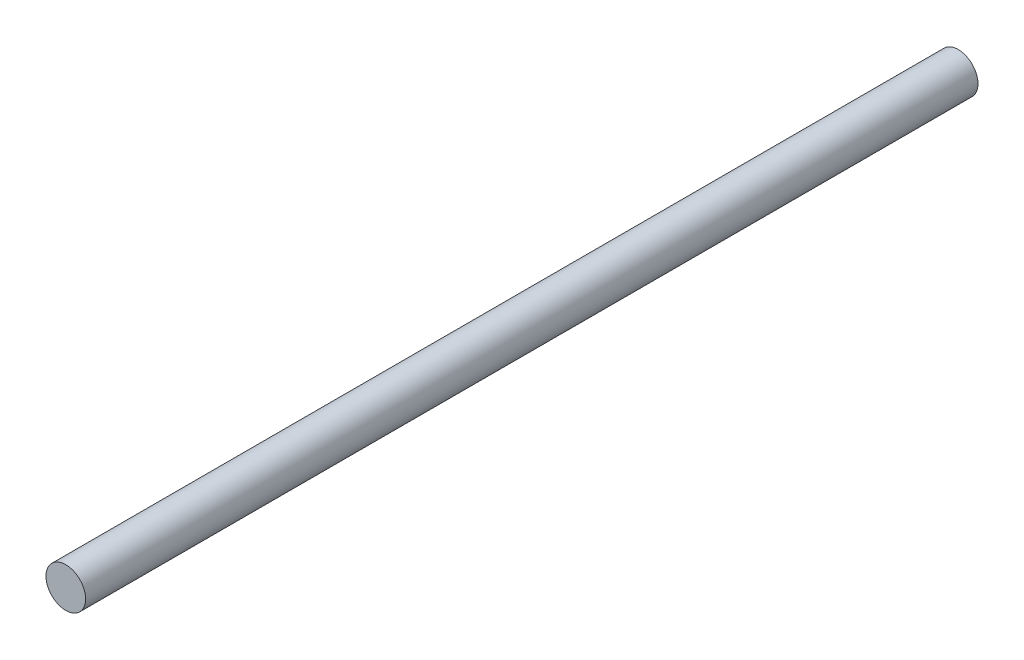
SolidWorks part; units mm, degrees
material "Литая нержавеющая сталь"
ref_plane "Спереди" through (0, 0, 0) normal (0, 0, 1) x (1, 0, 0)
ref_plane "Сверху" through (0, 0, 0) normal (0, 1, 0) x (1, 0, 0)
ref_plane "Справа" through (0, 0, 0) normal (1, 0, 0) x (0, 0, -1)
sketch "Эскиз1" plane through (0, 0, 0) normal (0, 0, 1) x (1, 0, 0)
  circle A1 centre (0, 0) radius 10
  dimension "D2" = 20
extrude "Вытянуть1" add sketch "Эскиз1" along normal blind 450
